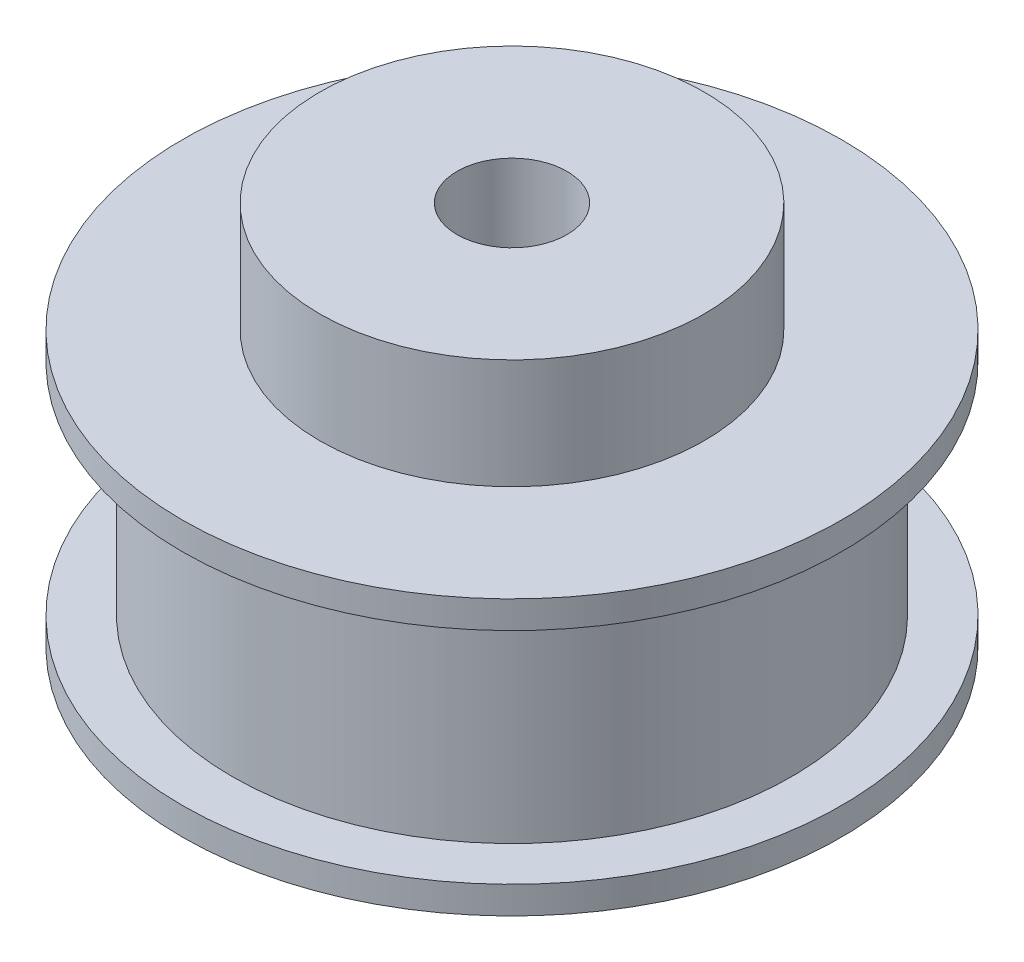
SolidWorks part; units mm, degrees
ref_plane "Front Plane" through (0, 0, 0) normal (0, 0, 1) x (1, 0, 0)
ref_plane "Top Plane" through (0, 0, 0) normal (0, 1, 0) x (1, 0, 0)
ref_plane "Right Plane" through (0, 0, 0) normal (1, 0, 0) x (0, 0, -1)
sketch "Sketch1" plane through (0, 0, 0) normal (0, 1, 0) x (1, 0, 0)
  circle A0 centre (0, 0) radius 19.05
  dimension "D1" = 38.1
extrude "Boss-Extrude1" add sketch "Sketch1" along normal blind 1.5875
sketch "Sketch2" plane through (0, 1.5875, 0) normal (0, 1, 0) x (1, 0, 0)
  circle A0 centre (0, 0) radius 16.1671
  dimension "D1" = 32.3342
extrude "Boss-Extrude2" add sketch "Sketch2" along normal blind 12.7
sketch "Sketch3" plane through (0, 14.2875, 0) normal (0, 1, 0) x (1, 0, 0)
  circle A0 centre (0, 0) radius 19.05
extrude "Boss-Extrude3" add sketch "Sketch3" along normal blind 1.5875
sketch "Sketch4" plane through (0, 15.875, 0) normal (0, 1, 0) x (1, 0, 0)
  circle A0 centre (0, 0) radius 11.1125
  dimension "D1" = 22.225
extrude "Boss-Extrude4" add sketch "Sketch4" along normal blind 6.35 contours A0
sketch "Sketch5" plane through (0, 22.225, 0) normal (0, 1, 0) x (1, 0, 0)
  circle A0 centre (0, 0) radius 3.175
  dimension "D1" = 6.35
extrude "Cut-Extrude1" cut sketch "Sketch5" against normal up to next
